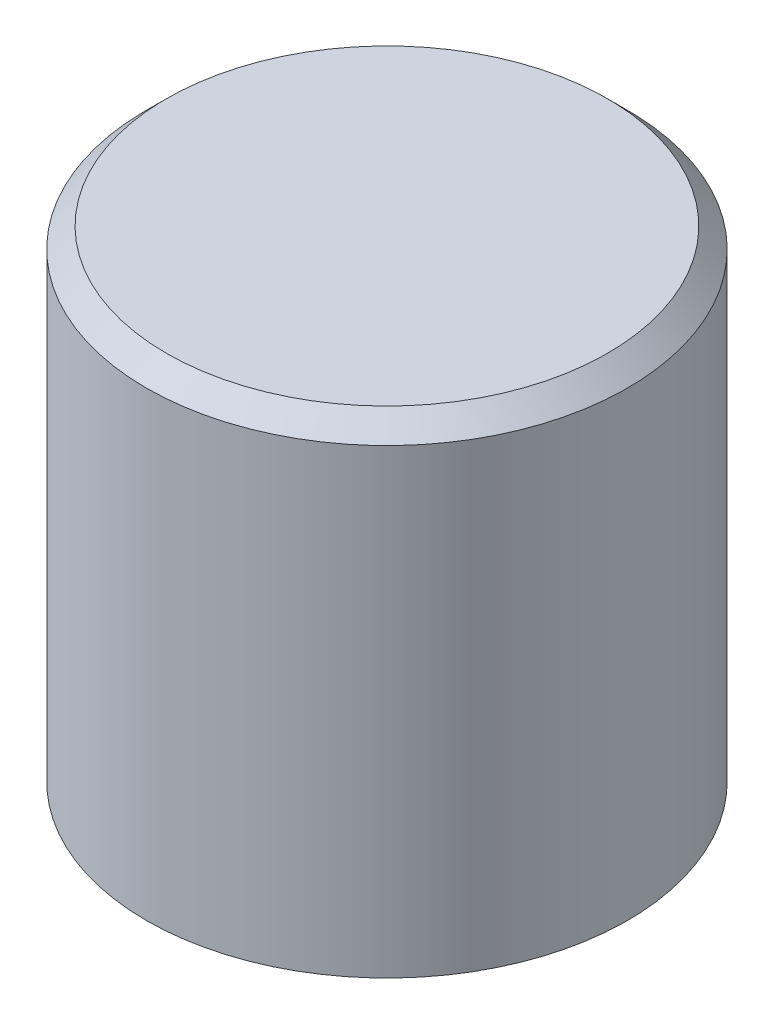
SolidWorks part; units mm, degrees
ref_plane "Front Plane" through (0, 0, 0) normal (0, 0, 1) x (1, 0, 0)
ref_plane "Top Plane" through (0, 0, 0) normal (0, 1, 0) x (1, 0, 0)
ref_plane "Right Plane" through (0, 0, 0) normal (1, 0, 0) x (0, 0, -1)
sketch "Sketch1" plane through (0, 0, 0) normal (0, 1, 0) x (1, 0, 0)
  circle A0 centre (0, 0) radius 6
  dimension "D1" = 12
extrude "Boss-Extrude1" add sketch "Sketch1" along normal blind 12
sketch "Sketch2" plane through (0, 0, 0) normal (0, 0, 1) x (1, 0, 0)
  line L0 (0, 0) -> (0, 8.5)
  line L1 (0, 8.5) -> (1.5, 8.5)
  line L2 (1.5, 8.5) -> (1.5, 4.1171)
  line L3 (1.5, 4.1171) -> (5, 3.5)
  line L4 (5, 3.5) -> (5, 0)
  line L6 (5, 0) -> (0, 0)
  line L7 (6, 0) -> (6, 12) construction
  line L8 (6, 0) -> (6, 12)
  line L9 (-6, 0) -> (6, 0) construction
  point P2 (0, 0)
  point P7 (0, 0)
  point P11 (0, 0)
  dimension "D1" = 1.5
  dimension "D2" = 8.5
  dimension "D3" = 3.5
  dimension "D4" = 80
  dimension "D5" = 5
revolve "Cut-Revolve1" cut sketch "Sketch2" angle 360 about L0
chamfer "Chamfer1" distance 0.1 angle 45 1 edges at (0, 4.1171, -1.5)
chamfer "Chamfer2" distance 0.5 angle 45 1 edges at (0, 12, 6)
